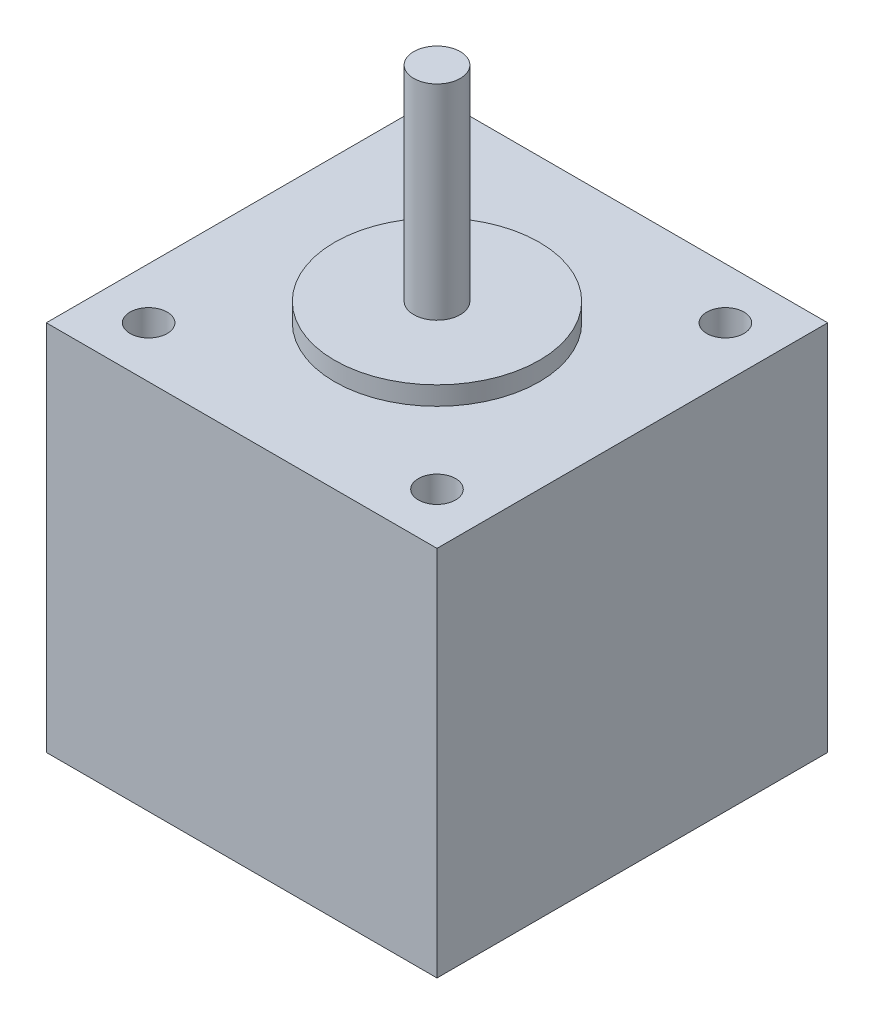
SolidWorks part; units mm, degrees
ref_plane "Front" through (0, 0, 0) normal (0, 0, 1) x (1, 0, 0)
ref_plane "Top" through (0, 0, 0) normal (0, 1, 0) x (1, 0, 0)
ref_plane "Right" through (0, 0, 0) normal (1, 0, 0) x (0, 0, -1)
sketch "Sketch1" plane through (0, 0, 0) normal (0, 1, 0) x (1, 0, 0)
  line L1 (-21, -21) -> (21, -21)
  line L2 (-21, -21) -> (-21, 21)
  line L3 (-21, 21) -> (21, 21)
  line L4 (21, -21) -> (21, 21)
  line L5 (-21, -21) -> (21, 21) construction
  line L6 (-21, 21) -> (21, -21) construction
  line L11 (-14.0711, -14.0711) -> (14.0711, 14.0711) construction
  line L12 (-14.0711, 14.0711) -> (14.0711, -14.0711) construction
  point P0 (0, 0)
  point P6 (0, 0)
  dimension "D1" = 42
extrude "Boss-Extrude1" add sketch "Sketch1" along normal blind 40
sketch "Sketch4" plane through (0, 40, 0) normal (0, 1, 0) x (1, 0, 0)
  line L1 (-15.5, -15.5) -> (15.5, -15.5) construction
  line L2 (-15.5, -15.5) -> (-15.5, 15.5) construction
  line L3 (-15.5, 15.5) -> (15.5, 15.5) construction
  line L4 (15.5, -15.5) -> (15.5, 15.5) construction
  line L5 (-15.5, -15.5) -> (15.5, 15.5) construction
  line L6 (-15.5, 15.5) -> (15.5, -15.5) construction
  circle A1 centre (-15.5, 15.5) radius 2
  circle A2 centre (15.5, 15.5) radius 2
  circle A3 centre (-15.5, -15.5) radius 2
  circle A4 centre (15.5, -15.5) radius 2
  point P0 (0, 0)
  point P9 (0, 0)
  point P11 (-17.0594, -15.5)
  point P12 (0, 0)
  point P14 (0, 0)
  dimension "D2" = 4
  dimension "D1" = 31
extrude "Cut-Extrude1" cut sketch "Sketch4" against normal blind 4.5
sketch "Sketch2" plane through (0, 40, 0) normal (0, 1, 0) x (1, 0, 0)
  circle A0 centre (0, 0) radius 11
  dimension "D1" = 22
extrude "Boss-Extrude2" add sketch "Sketch2" along normal blind 2
sketch "Sketch3" plane through (0, 42, 0) normal (0, 1, 0) x (1, 0, 0)
  circle A0 centre (0, 0) radius 2.5
  dimension "D1" = 5
extrude "Boss-Extrude3" add sketch "Sketch3" along normal blind 22
